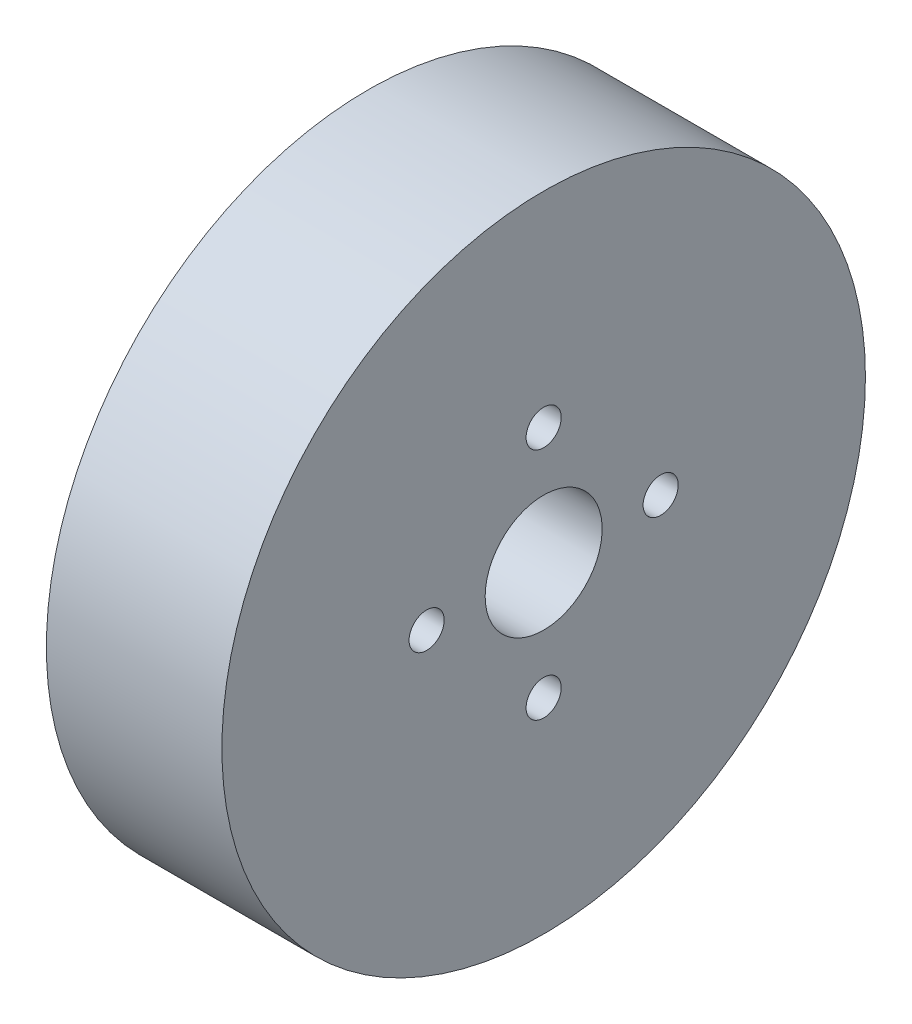
SolidWorks part; units mm, degrees
ref_plane "前视基准面" through (0, 0, 0) normal (0, 0, 1) x (1, 0, 0)
ref_plane "上视基准面" through (0, 0, 0) normal (0, 1, 0) x (1, 0, 0)
ref_plane "右视基准面" through (0, 0, 0) normal (1, 0, 0) x (0, 0, -1)
sketch "草图1" plane through (0, 0, 0) normal (1, 0, 0) x (0, 0, -1)
  circle A0 centre (-18.7953, 14.0619) radius 27.5
  dimension "D1" = 55
extrude "凸台-拉伸1" add sketch "草图1" along normal blind 15
sketch "草图2" plane through (0, 0, 0) normal (-1, 0, 0) x (0, 0, 1)
  line L0 (8.7953, 14.0619) -> (28.7953, 14.0619) construction
  line L1 (18.7953, 24.0619) -> (18.7953, 4.0619) construction
  circle A0 centre (18.7953, 14.0619) radius 5
  circle A1 centre (18.7953, 24.0619) radius 1.5
  circle A2 centre (28.7953, 14.0619) radius 1.5
  circle A3 centre (8.7953, 14.0619) radius 1.5
  circle A4 centre (18.7953, 4.0619) radius 1.5
  circle A5 centre (18.7953, 14.0619) radius 27.5 construction
  dimension "D1" = 10
  dimension "D2" = 0
  dimension "D3" = 10
  dimension "D4" = 3
  dimension "D5" = 10
  dimension "D6" = 0
  dimension "D7" = 10
  dimension "D9" = 10
  dimension "D10" = 3
  dimension "D11" = 3
  dimension "D12" = 3
  dimension "D8" = 0
extrude "切除-拉伸1" cut sketch "草图2" against normal up to next
